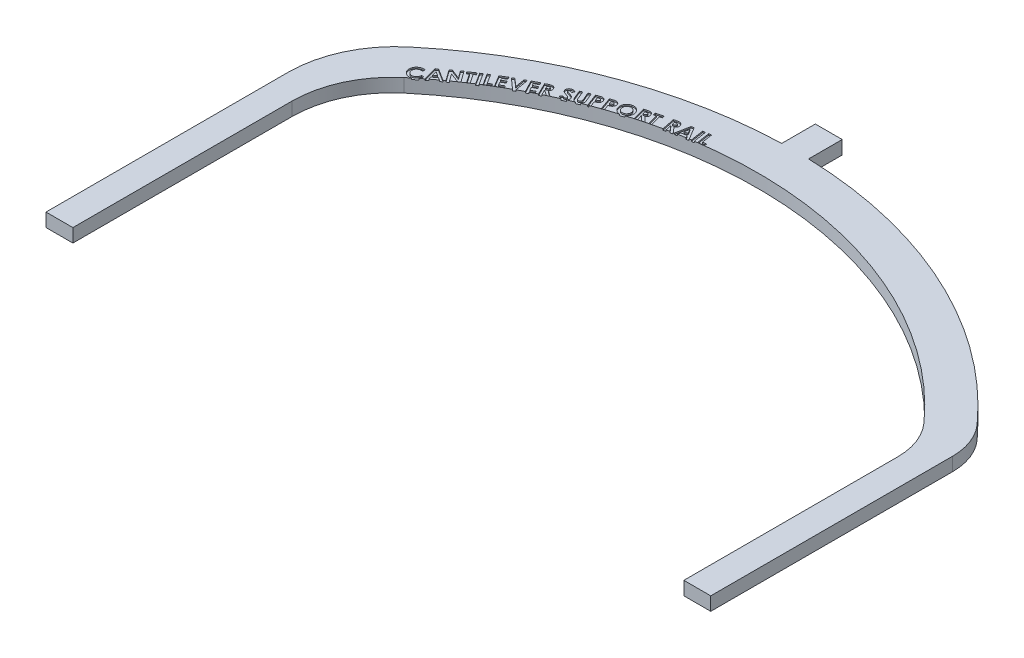
SolidWorks part; units mm, degrees
ref_plane "Front Plane" through (0, 0, 0) normal (0, 0, 1) x (1, 0, 0)
ref_plane "Top Plane" through (0, 0, 0) normal (0, 1, 0) x (1, 0, 0)
ref_plane "Right Plane" through (0, 0, 0) normal (1, 0, 0) x (0, 0, -1)
sketch "Sketch1" plane through (0, 0, 0) normal (0, 1, 0) x (1, 0, 0)
  line L2 (1563.5351, 125.0327) -> (1563.5351, 279.8321) construction
  line L3 (1550.8351, 541.3991) -> (1550.8351, 573.1491)
  line L4 (1550.8351, 573.1491) -> (1576.2351, 573.1491)
  line L5 (1576.2351, 573.1491) -> (1576.2351, 541.3991)
  line L6 (1295.7755, 444.1362) -> (1318.633, 416.8957) construction
  line L7 (1259.4827, 137.7061) -> (1284.8827, 137.7061)
  line L8 (1259.4827, 137.7061) -> (1259.4827, 366.3061)
  line L10 (1284.8827, 137.7061) -> (1284.8827, 344.5179)
  line L12 (1862.0789, 339.8384) -> (1862.0789, 137.7061)
  line L13 (1862.0789, 137.7061) -> (1887.4789, 137.7061)
  line L14 (1887.4789, 366.3061) -> (1887.4789, 137.7061)
  line L15 (1873.0995, 403.7658) -> (1846.6732, 379.9715) construction
  arc A0 (1295.7755, 444.1362) -> (1550.8351, 541.3991) centre (1563.5351, 125.0327) cw
  arc A1 (1318.633, 416.8957) -> (1846.6732, 379.9715) centre (1563.5351, 125.0327) cw
  arc A2 (1576.2351, 541.3991) -> (1873.0995, 403.7658) centre (1563.5351, 125.0327) cw
  arc A3 (1295.7755, 444.1362) -> (1259.4827, 366.3061) centre (1361.0827, 366.3061) ccw
  arc A4 (1318.633, 416.8957) -> (1284.8827, 344.5179) centre (1379.3651, 344.5179) ccw
  arc A5 (1846.6732, 379.9715) -> (1862.0789, 339.8384) centre (1802.1009, 339.8384) cw
  arc A6 (1873.0995, 403.7658) -> (1887.4789, 366.3061) centre (1831.4963, 366.3061) cw
  circle A7 centre (1512.7351, 122.4927) radius 60.7995 construction
  point P25 (576.6283, -161.5469)
  point P26 (0, 0)
  point P28 (627.4283, -138.3114)
  dimension "D1" = 381
  dimension "D4" = 101.6
  dimension "D2" = 35.56
  dimension "D3" = 228.6
  dimension "D5" = 25.4
  dimension "D6" = 31.75
  dimension "D7" = 40
  dimension "D8" = 48
  dimension "D9" = 50.8
  dimension "D10" = 2.54
  dimension "D11" = 25.4
  dimension "D12" = 25.4
extrude "Boss-Extrude1" add sketch "Sketch1" along normal blind 12.7
sketch "Sketch2" plane through (0, 12.7, 0) normal (0, 1, 0) x (1, 0, 0)
  text T0 "CANTILEVER SUPPORT RAIL" font "Century Gothic" height 12.7
extrude "Cut-Extrude1" cut sketch "Sketch2" against normal blind 1.27
